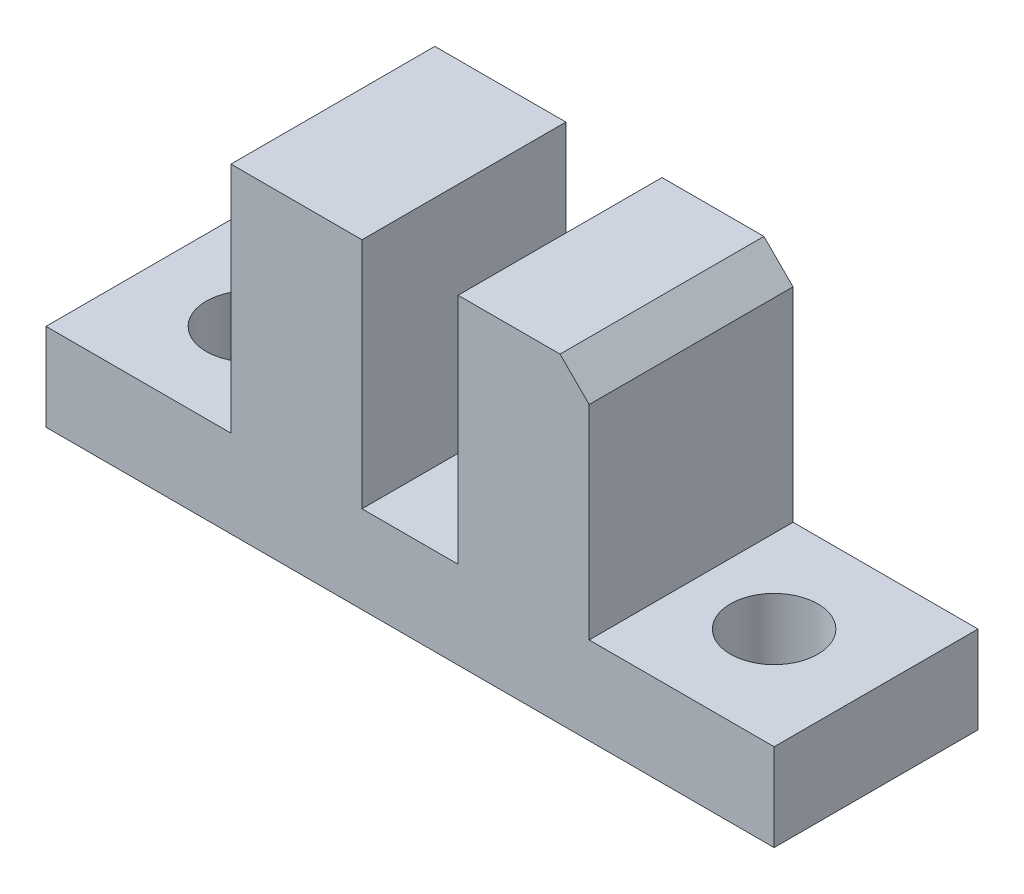
SolidWorks part; units mm, degrees
ref_plane "Front Plane" through (0, 0, 0) normal (0, 0, 1) x (1, 0, 0)
ref_plane "Top Plane" through (0, 0, 0) normal (0, 1, 0) x (1, 0, 0)
ref_plane "Right Plane" through (0, 0, 0) normal (1, 0, 0) x (0, 0, -1)
sketch "Sketch1" plane through (0, 0, 0) normal (0, 1, 0) x (1, 0, 0)
  line L0 (0, 0) -> (50000, 0) construction
  line L1 (-12.5, -3.5) -> (12.5, -3.5)
  line L2 (-12.5, -3.5) -> (-12.5, 3.5)
  line L3 (-12.5, 3.5) -> (12.5, 3.5)
  line L4 (12.5, -3.5) -> (12.5, 3.5)
  line L5 (-12.5, -3.5) -> (12.5, 3.5) construction
  line L6 (-12.5, 3.5) -> (12.5, -3.5) construction
  line L7 (0, 0) -> (0, 50000) construction
  circle A0 centre (9, 0) radius 1.5
  circle A1 centre (-9, 0) radius 1.5
  point P0 (0, 0)
  dimension "D3" = 3
  dimension "D4" = 3.5
  dimension "D1" = 25
  dimension "D2" = 7
extrude "Boss-Extrude1" add sketch "Sketch1" along normal blind 3
sketch "Sketch2" plane through (0, 0, 0) normal (0, -1, 0) x (1, 0, 0)
  line L0 (-12.5, 3.5) -> (12.5, 3.5) construction
  line L1 (-6.15, -3.5) -> (-1.65, -3.5)
  line L2 (-6.15, -3.5) -> (-6.15, 3.5)
  line L3 (-6.15, 3.5) -> (-1.65, 3.5)
  line L4 (6.15, -3.5) -> (6.15, 3.5)
  line L5 (-6.15, -3.5) -> (6.15, 3.5) construction
  line L6 (-6.15, 3.5) -> (6.15, -3.5) construction
  line L7 (1.65, 3.5) -> (6.15, 3.5)
  line L9 (-1.65, -3.5) -> (-1.65, 3.5)
  line L10 (1.65, -3.5) -> (6.15, -3.5)
  line L11 (1.65, -3.5) -> (1.65, 3.5)
  line L12 (-1.65, -3.5) -> (1.65, 3.5) construction
  line L13 (-1.65, 3.5) -> (1.65, -3.5) construction
  point P0 (0, 0)
  point P8 (0, 0)
  dimension "D1" = 12.3
  dimension "D2" = 4.5
  dimension "D3" = 4.5
extrude "Boss-Extrude2" add sketch "Sketch2" against normal blind 11
chamfer "Chamfer1" distance 1 angle 45 1 edges at (6.15, 11, 0)
